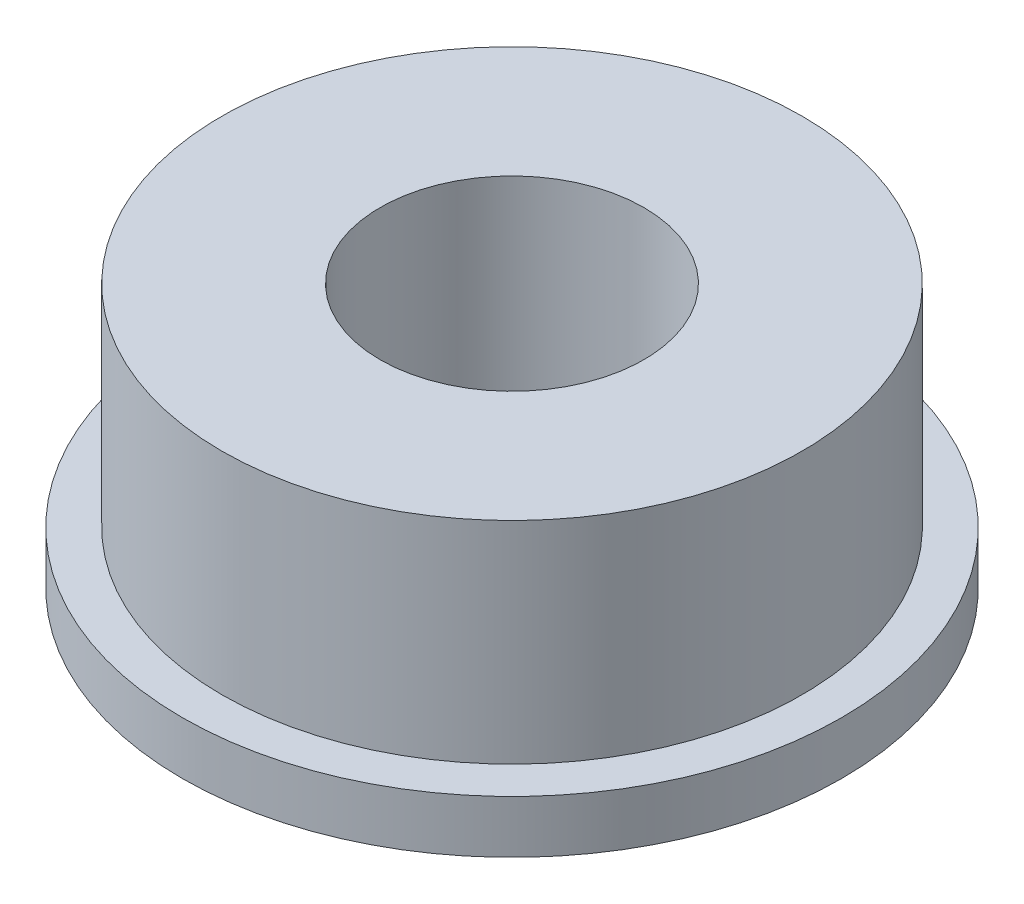
SolidWorks part; units mm, degrees
ref_plane "前视基准面" through (0, 0, 0) normal (0, 0, 1) x (1, 0, 0)
ref_plane "上视基准面" through (0, 0, 0) normal (0, 1, 0) x (1, 0, 0)
ref_plane "右视基准面" through (0, 0, 0) normal (1, 0, 0) x (0, 0, -1)
sketch "Sketch1" plane through (0, 0, 0) normal (0, 1, 0) x (1, 0, 0)
  circle A0 centre (0, 0) radius 5.5
  circle A1 centre (0, 0) radius 2.5
extrude "Boss-Extrude1" add sketch "Sketch1" along normal blind 4
sketch "Sketch2" plane through (0, 0, 0) normal (0, -1, 0) x (1, 0, 0)
  circle A0 centre (0, 0) radius 2.5 construction
  circle A1 centre (0, 0) radius 2.5
  circle A2 centre (0, 0) radius 6.25
extrude "Boss-Extrude2" add sketch "Sketch2" along normal blind 1
